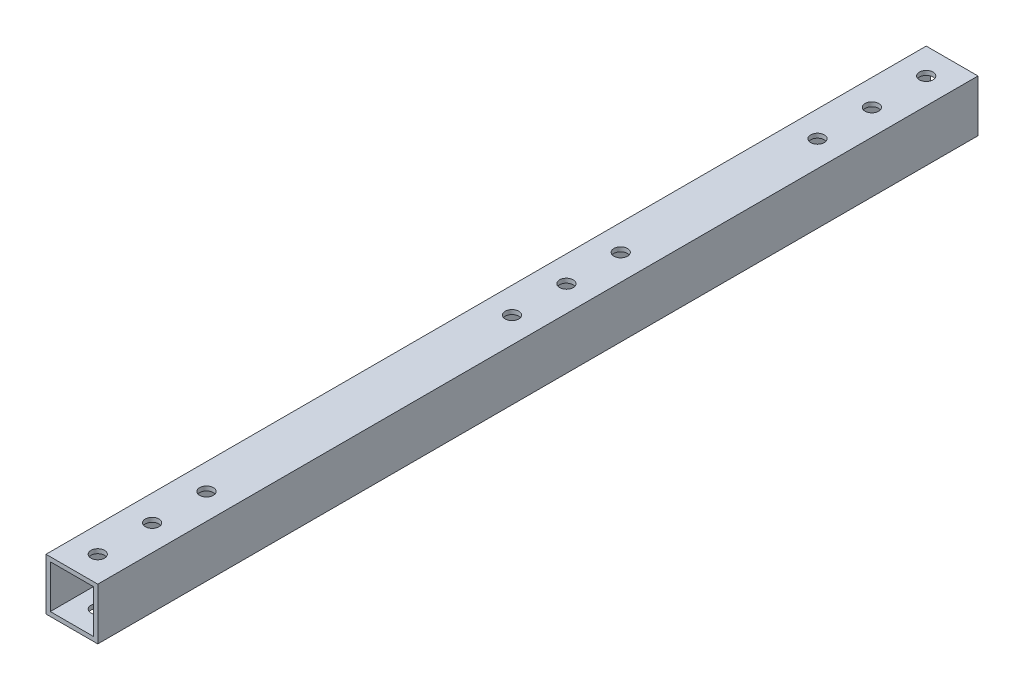
SolidWorks part; units mm, degrees
material "6061 Alloy"
ref_plane "Front Plane" through (0, 0, 0) normal (0, 0, 1) x (1, 0, 0)
ref_plane "Top Plane" through (0, 0, 0) normal (0, 1, 0) x (1, 0, 0)
ref_plane "Right Plane" through (0, 0, 0) normal (1, 0, 0) x (0, 0, -1)
sketch "Sketch1" plane through (0, 0, 0) normal (0, 0, 1) x (1, 0, 0)
  line L1 (-7.9375, -7.9375) -> (7.9375, -7.9375)
  line L2 (-7.9375, -7.9375) -> (-7.9375, 7.9375)
  line L3 (-7.9375, 7.9375) -> (7.9375, 7.9375)
  line L4 (7.9375, -7.9375) -> (7.9375, 7.9375)
  line L5 (-7.9375, -7.9375) -> (7.9375, 7.9375) construction
  line L6 (-7.9375, 7.9375) -> (7.9375, -7.9375) construction
  line L7 (-9.525, -9.525) -> (9.525, -9.525)
  line L8 (-9.525, -9.525) -> (-9.525, 9.525)
  line L9 (-9.525, 9.525) -> (9.525, 9.525)
  line L10 (9.525, -9.525) -> (9.525, 9.525)
  line L11 (-9.525, -9.525) -> (9.525, 9.525) construction
  line L12 (-9.525, 9.525) -> (9.525, -9.525) construction
  point P0 (0, 0)
  point P6 (0, 0)
  dimension "D1" = 19.05
  dimension "D2" = 19.05
  dimension "D3" = 1.5875
  dimension "D4" = 1.5875
extrude "Boss-Extrude1" add sketch "Sketch1" along normal mid plane 323.85
extrude "Cut-Extrude1" cut sketch "Sketch2" against normal blind 30
sketch "Sketch2" plane through (-206.375, 13.525, 0) normal (0, 1, 0) x (0, 0, -1)
  circle A0 centre (152.4, -206.375) radius 2.5
  circle A1 centre (152.4, -186.375) radius 2.5
  circle A2 centre (152.4, -166.375) radius 2.5
  circle A3 centre (132.4, -206.375) radius 2.5
  circle A4 centre (112.4, -206.375) radius 2.5
mirror "Mirror1" of "Cut-Extrude1"
extrude "Cut-Extrude2" cut sketch "Sketch3" against normal blind 30
sketch "Sketch3" plane through (-206.375, 13.525, 0) normal (0, 1, 0) x (0, 0, -1)
  circle A0 centre (0, -206.375) radius 2.5
  circle A1 centre (0, -186.375) radius 2.5
  circle A2 centre (0, -166.375) radius 2.5
  circle A3 centre (20, -206.375) radius 2.5
  circle A4 centre (40, -206.375) radius 2.5
